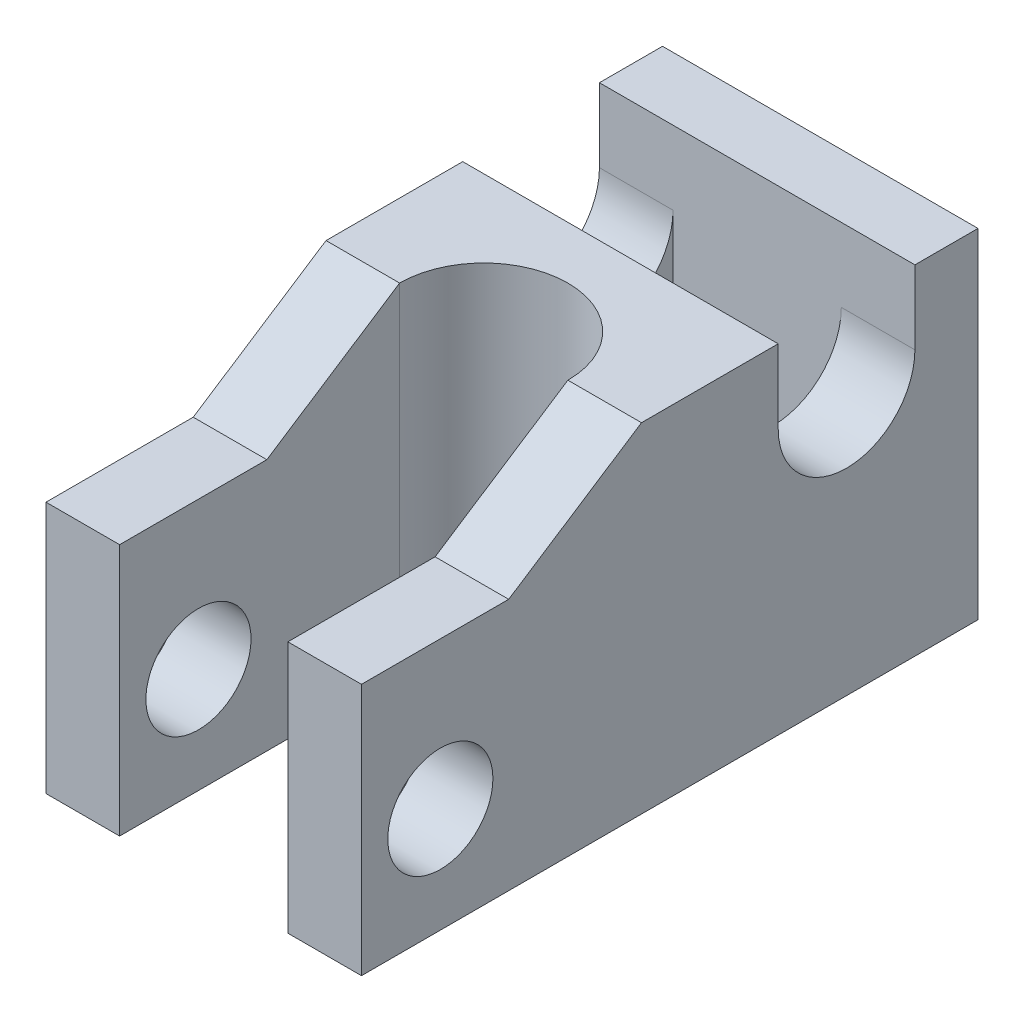
SolidWorks part; units mm, degrees
ref_plane "Front Plane" through (0, 0, 0) normal (0, 0, 1) x (1, 0, 0)
ref_plane "Top Plane" through (0, 0, 0) normal (0, 1, 0) x (1, 0, 0)
ref_plane "Right Plane" through (0, 0, 0) normal (1, 0, 0) x (0, 0, -1)
sketch "Sketch1" plane through (0, 0, 0) normal (1, 0, 0) x (0, 0, -1)
  line L0 (-61.382, 0) -> (-61.382, 48)
  line L1 (-61.382, 48) -> (-33.382, 48)
  line L2 (-33.382, 48) -> (-8.1223, 64.4609)
  line L5 (43.8777, 64.4609) -> (55.8777, 64.4609)
  line L6 (55.8777, 64.4609) -> (55.8777, 0)
  line L8 (30.8777, 64.4609) -> (30.8777, 50.4609) construction
  line L9 (43.8777, 64.4609) -> (43.8777, 50.4609)
  line L10 (17.8777, 64.4609) -> (17.8777, 50.4609)
  line L11 (-61.382, 0) -> (55.8777, 0)
  line L12 (-8.1223, 64.4609) -> (17.8777, 64.4609)
  arc A1 (43.8777, 64.4609) -> (17.8777, 64.4609) centre (30.8777, 64.4609) ccw
  arc A2 (17.8777, 50.4609) -> (43.8777, 50.4609) centre (30.8777, 50.4609) ccw
  circle A3 centre (-46.382, 20) radius 10
  point P12 (30.8777, 57.4609)
  dimension "D6" = 13
  dimension "D8" = 15
  dimension "D2" = 48
  dimension "D3" = 28
  dimension "D7" = 25
  dimension "D10" = 14
extrude "Boss-Extrude1" add sketch "Sketch1" against normal blind 14 contours A2 L10 L12 L2 L1 L0 L11 L6 L5 L9 A3
ref_plane "Plane1" through (-30, 0, 0) normal (-1, 0, 0) x (0, 0, 1)
mirror "Mirror4" about plane through (-30, 0, 0) normal (-1, 0, 0) of bodies 101
sketch "Sketch2" plane through (0, 64.4609, 0) normal (0, 1, 0) x (1, 0, 0)
  line L0 (-46, 17.8777) -> (-14, 17.8777)
  line L1 (-60, -8.1223) -> (-60, 17.8777)
  line L2 (-60, 17.8777) -> (0, 17.8777)
  line L3 (0, 17.8777) -> (0, -8.1223)
  line L4 (0, -8.1223) -> (-14, -8.1223)
  line L5 (-60, -8.1223) -> (-46, -8.1223)
  arc A0 (-46, -8.1223) -> (-14, -8.1223) centre (-30, -8.1223) cw
  line M1 (-60, 17.8777) -> (-60, -8.1223)
  line M2 (-60, -8.1223) -> (-46, -8.1223)
  line M3 (-46, -8.1223) -> (-46, 17.8777)
  line M4 (-46, 17.8777) -> (-60, 17.8777)
extrude "Boss-Extrude2" add sketch "Sketch2" against normal blind 64 contours A0 L4 L3 L2 L0 M3 | M4 M1 M2 M3
sketch "Sketch3" plane through (0, 0, 0) normal (1, 0, 0) x (0, 0, -1)
  line L3 (18.0823, 63.9914) -> (43.673, 63.9914)
sketch "Sketch4" plane through (0, 64.4609, 0) normal (0, 1, 0) x (1, 0, 0)
  line L5 (-60, 43.8777) -> (-60, 55.8777)
  line L6 (-60, 43.8777) -> (-60, 55.8777) construction
  line L7 (-60, 55.8777) -> (0, 55.8777)
  line L8 (0, 55.8777) -> (0, 43.8777)
  line L9 (0, 43.8777) -> (-60, 43.8777)
extrude "Boss-Extrude4" add sketch "Sketch4" against normal blind 64
